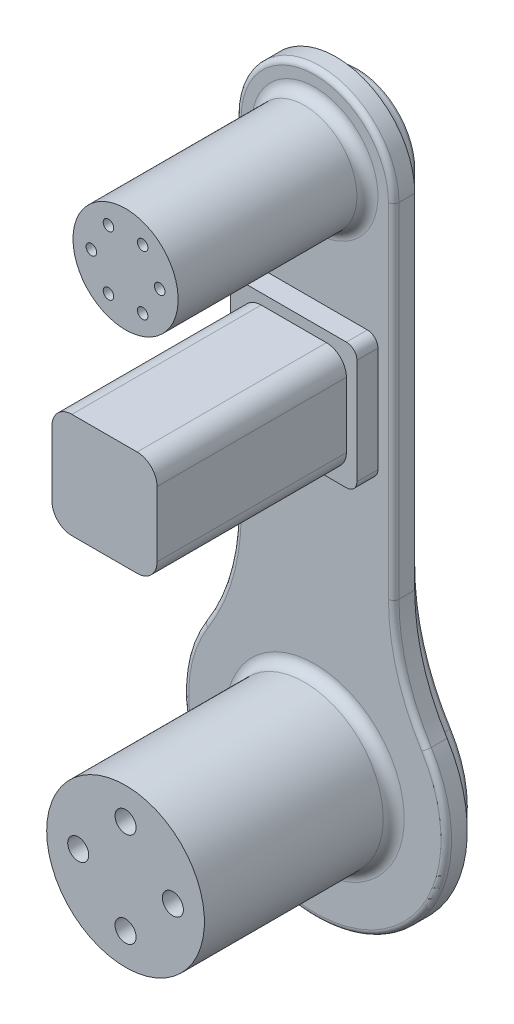
SolidWorks part; units mm, degrees
ref_plane "Front Plane" through (0, 0, 0) normal (0, 0, 1) x (1, 0, 0)
ref_plane "Top Plane" through (0, 0, 0) normal (0, 1, 0) x (1, 0, 0)
ref_plane "Right Plane" through (0, 0, 0) normal (1, 0, 0) x (0, 0, -1)
sketch "Sketch1" plane through (0, 0, 0) normal (0, 0, 1) x (1, 0, 0)
  line L0 (0, -250) -> (0, 250) construction
  circle A0 centre (0, 250) radius 50
  circle A1 centre (0, -250) radius 75
  point P4 (0, 0)
  dimension "D1" = 100
  dimension "D2" = 150
  dimension "D3" = 500
extrude "Boss-Extrude1" add sketch "Sketch1" along normal mid plane 180
sketch "Sketch2" plane through (0, 0, 90) normal (0, 0, 1) x (1, 0, 0)
  circle A0 centre (0, -250) radius 45 construction
  circle A1 centre (-45, -250) radius 10
  circle A2 centre (0, -205) radius 10
  circle A3 centre (45, -250) radius 10
  circle A4 centre (0, -295) radius 10
  circle A5 centre (0, 250) radius 32.5 construction
  circle A6 centre (-32.5, 250) radius 5
  circle A7 centre (-16.25, 278.1458) radius 5
  circle A8 centre (16.25, 278.1458) radius 5
  circle A9 centre (32.5, 250) radius 5
  circle A10 centre (16.25, 221.8542) radius 5
  circle A11 centre (-16.25, 221.8542) radius 5
  point P14 (0, -250)
  point P26 (0, 250)
  dimension "D1" = 20
  dimension "D2" = 90
  dimension "D4" = 10
  dimension "D5" = 65
  dimension "D3" = 4
  dimension "D6" = 6
extrude "Cut-Extrude1" cut sketch "Sketch2" against normal blind 40
sketch "Sketch3" plane through (0, 0, -90) normal (0, 0, -1) x (-1, 0, 0)
  line L0 (-75, 250) -> (-75, -76.7949)
  line L1 (0, 0) -> (0, 250) construction
  line L2 (75, 250) -> (75, -76.7949)
  arc A0 (75, 250) -> (-75, 250) centre (0, 250) ccw
  arc A1 (-105.7692, -183.3827) -> (105.7692, -183.3827) centre (0, -250) ccw
  arc A2 (-75, -76.7949) -> (-105.7692, -183.3827) centre (-275, -76.7949) cw
  arc A3 (75, -76.7949) -> (105.7692, -183.3827) centre (275, -76.7949) ccw
  dimension "D1" = 75
  dimension "D2" = 125
  dimension "D3" = 200
extrude "Boss-Extrude2" add sketch "Sketch3" along normal blind 20
sketch "Sketch4" plane through (0, 0, -110) normal (0, 0, -1) x (-1, 0, 0)
  line L4 (-55, 250) -> (-55, -76.7949)
  line L5 (55, -76.7949) -> (55, 250)
  line L6 (-55, 250) -> (-55, -76.7949)
  line L7 (55, -76.7949) -> (55, 250)
  arc A8 (55, 250) -> (-55, 250) centre (0, 250) ccw
  arc A9 (-88.8462, -194.0414) -> (-55, -76.7949) centre (-275, -76.7949) ccw
  arc A10 (-88.8462, -194.0414) -> (88.8462, -194.0414) centre (0, -250) ccw
  arc A11 (55, -76.7949) -> (88.8462, -194.0414) centre (275, -76.7949) ccw
  arc A12 (55, 250) -> (-55, 250) centre (0, 250) ccw
  arc A13 (-88.8462, -194.0414) -> (-55, -76.7949) centre (-275, -76.7949) ccw
  arc A14 (-88.8462, -194.0414) -> (88.8462, -194.0414) centre (0, -250) ccw
  arc A15 (55, -76.7949) -> (88.8462, -194.0414) centre (275, -76.7949) ccw
  dimension "D1" = 20
extrude "Boss-Extrude3" add sketch "Sketch4" along normal blind 20
fillet "Fillet1" radius 19 6 edges at (0, 305, -110) (-55, 86.6025, -110) (-63.6308, -137.8119, -110) (0, -355, -110) (63.6308, -137.8119, -110) (55, 86.6025, -110)
sketch "Sketch5" plane through (0, 0, -90) normal (0, 0, 1) x (1, 0, 0)
  line L0 (0, 0) -> (0, 75) construction
  line L2 (-60, 15) -> (60, 15)
  line L3 (-60, 15) -> (-60, 135)
  line L4 (-60, 135) -> (60, 135)
  line L5 (60, 15) -> (60, 135)
  line L6 (-60, 15) -> (60, 135) construction
  line L7 (-60, 135) -> (60, 15) construction
  circle A0 centre (0, 250) radius 50 construction
  dimension "D1" = 120
  dimension "D2" = 120
  dimension "D3" = 115
extrude "Boss-Extrude4" add sketch "Sketch5" along normal blind 20
sketch "Sketch6" plane through (0, 0, -70) normal (0, 0, 1) x (1, 0, 0)
  line L8 (50, 25) -> (50, 125)
  line L9 (50, 125) -> (-50, 125)
  line L10 (-50, 125) -> (-50, 25)
  line L11 (-50, 25) -> (50, 25)
  line L12 (50, 25) -> (50, 125)
  line L13 (50, 125) -> (-50, 125)
  line L14 (-50, 125) -> (-50, 25)
  line L15 (-50, 25) -> (50, 25)
  dimension "D1" = 10
extrude "Boss-Extrude5" add sketch "Sketch6" along normal blind 180
fillet "Fillet2" radius 19 4 edges at (-50, 25, 20) (-50, 125, 20) (50, 25, 20) (50, 125, 20)
fillet "Fillet3" radius 10 4 edges at (-60, 15, -80) (-60, 135, -80) (60, 15, -80) (60, 135, -80)
fillet "Fillet4" radius 10 2 edges at (50, 250, -90) (-75, -250, -90)
fillet "Fillet5" radius 5 6 edges at (0, 325, -90) (-75, 86.6025, -90) (-82.8462, -132.2649, -90) (0, -375, -90) (82.8462, -132.2649, -90) (75, 86.6025, -90)
sketch "Sketch7" plane through (0, 0, -130) normal (0, 0, -1) x (-1, 0, 0)
  line L0 (-11.6639, 247.1083) -> (-11.6639, -302.5925) construction
  text T0 "SOLIDWORKS TUTORIAL HP" font "Century Gothic" height 30
  point P3 (-9.037, 247.1083)
  point P4 (-11.6639, -302.5925)
extrude "Boss-Extrude6" add sketch "Sketch7" along normal blind 0.1
